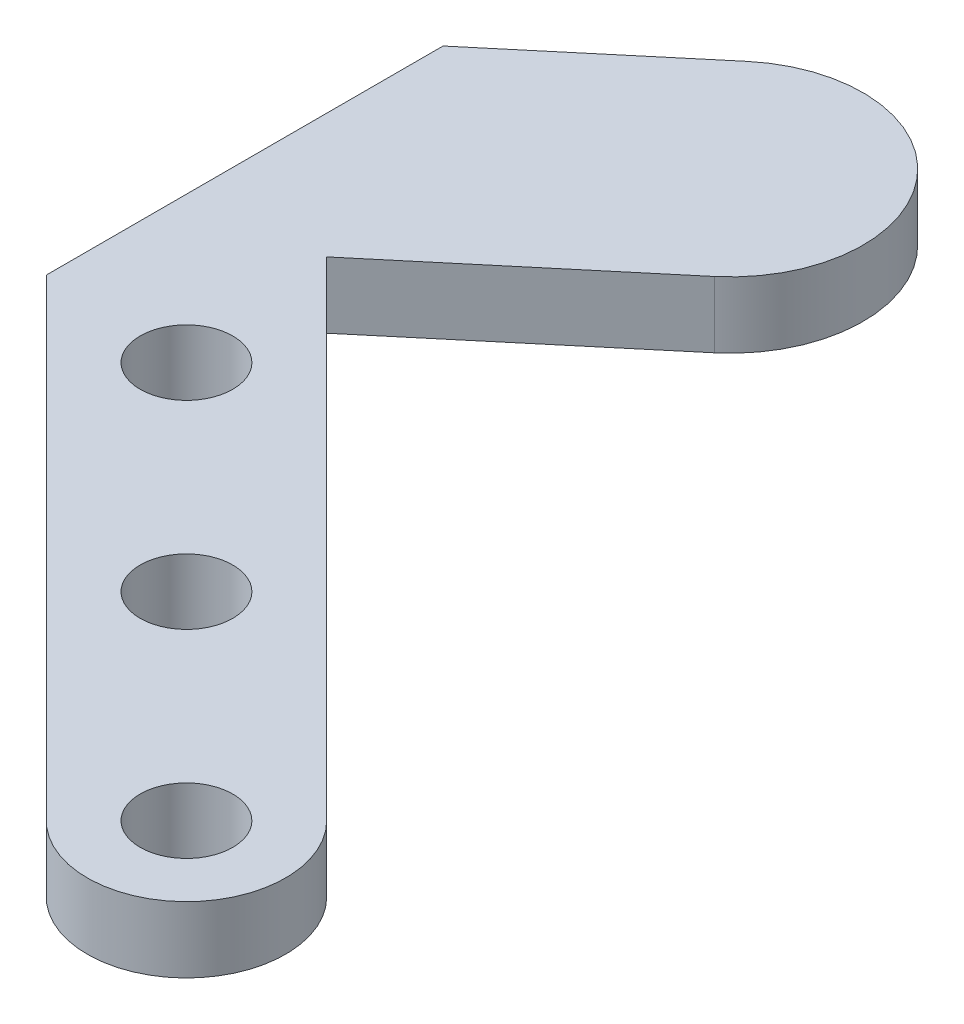
SolidWorks part; units mm, degrees
ref_plane "Front Plane" through (0, 0, 0) normal (0, 0, 1) x (1, 0, 0)
ref_plane "Top Plane" through (0, 0, 0) normal (0, 1, 0) x (1, 0, 0)
ref_plane "Right Plane" through (0, 0, 0) normal (1, 0, 0) x (0, 0, -1)
sketch "Sketch1" plane through (0, 0, 0) normal (0, 1, 0) x (1, 0, 0)
  line L0 (-42.331, 0) -> (141.7333, 0) construction
  line L1 (-42.331, 0) -> (-10.4448, 26.7557)
  line L2 (-36.1564, 57.3974) -> (-61.1564, 36.42)
  line L3 (-61.1564, 36.42) -> (-61.1564, -23.58)
  line L5 (-42.331, 0) -> (31.5184, -73.8494)
  line L6 (9.8436, -94.58) -> (-61.1564, -23.58)
  arc A0 (-10.4448, 26.7557) -> (-36.1564, 57.3974) centre (-23.3006, 42.0766) ccw
  arc A1 (31.5184, -73.8494) -> (9.8436, -94.58) centre (20.9118, -84.456) cw
  circle A2 centre (20.9118, -84.456) radius 7
  circle A3 centre (-9.0882, -54.456) radius 7
  circle A4 centre (-39.0882, -24.456) radius 7
  dimension "D1" = 40
  dimension "D5" = 25
  dimension "D8" = 14
  dimension "D9" = 15
  dimension "D2" = 45
  dimension "D3" = 45
  dimension "D4" = 40
  dimension "D6" = 60
  dimension "D7" = 71
  dimension "D11" = 30
  dimension "D10" = 3
extrude "Boss-Extrude1" add sketch "Sketch1" along normal blind 10
